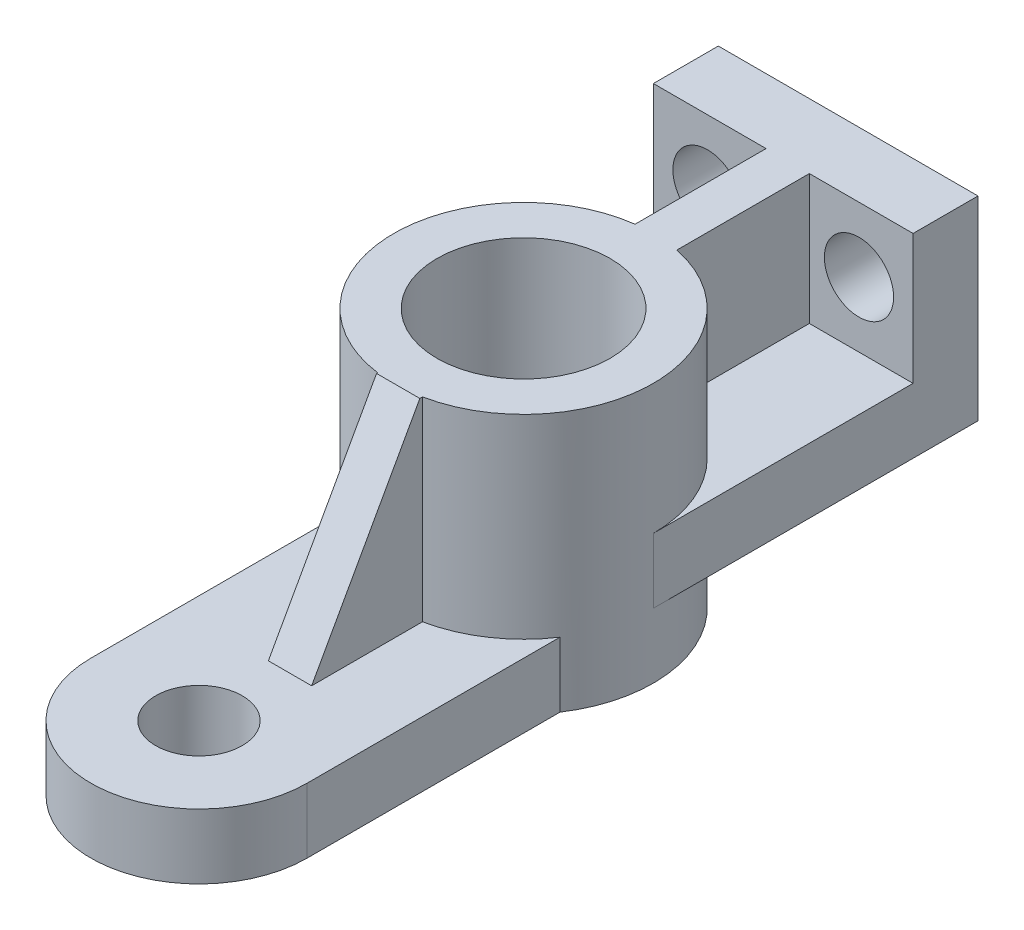
SolidWorks part; units mm, degrees
ref_plane "Front" through (0, 0, 0) normal (0, 0, 1) x (1, 0, 0)
ref_plane "Top" through (0, 0, 0) normal (0, 1, 0) x (1, 0, 0)
ref_plane "Right" through (0, 0, 0) normal (1, 0, 0) x (0, 0, -1)
sketch "Sketch1" plane through (0, 0, 0) normal (0, 0, 1) x (1, 0, 0)
  line L1 (0, 0) -> (-1524, 0)
  line L2 (0, 0) -> (0, 1143)
  line L3 (0, 1143) -> (-1524, 1143)
  line L4 (-1524, 0) -> (-1524, 1143)
  dimension "D1" = 1524
  dimension "D2" = 1143
extrude "Boss-Extrude1" add sketch "Sketch1" along normal blind 381
sketch "Sketch4" plane through (0, 0, 381) normal (0, 0, 1) x (1, 0, 0)
  line L0 (-1206.5, 762) -> (-317.5, 762) construction
  line L1 (0, 1143) -> (-1524, 1143) construction
  line L2 (-1524, 1143) -> (-1524, 0) construction
  circle A0 centre (-317.5, 762) radius 203.2
  circle A1 centre (-1206.5, 762) radius 203.2
  point P4 (-762, 762)
  point P7 (0, 0)
  dimension "D1" = 406.4
  dimension "D4" = 762
  dimension "D2" = 381
  dimension "D3" = 889
extrude "Cut-Extrude1" cut sketch "Sketch4" against normal through all
sketch "Sketch5" plane through (0, 1143, 0) normal (0, 1, 0) x (1, 0, 0)
  line L0 (0, -381) -> (-1524, -381) construction
  line L1 (-1524, -381) -> (-1524, 0) construction
  circle A0 centre (-762, -1905) radius 762
  dimension "D1" = 1524
  dimension "D2" = 1524
extrude "Boss-Extrude2" add sketch "Sketch5" against normal blind 1524 separate body
sketch "Sketch6" plane through (0, 0, 381) normal (0, 0, 1) x (1, 0, 0)
  line L0 (-1524, 1143) -> (-1524, 0) construction
  line L1 (0, 0) -> (-1524, 0)
  line L2 (0, 0) -> (0, 381)
  line L3 (0, 381) -> (-1524, 381)
  line L4 (-1524, 0) -> (-1524, 381)
  dimension "D1" = 381
extrude "Boss-Extrude3" add sketch "Sketch6" along normal blind 1524
sketch "Sketch8" plane through (0, 381, 0) normal (0, 1, 0) x (1, 0, 0)
  line L0 (0, -381) -> (-1524, -381) construction
  line L1 (-608.7231, -381) -> (-862.7231, -381)
  line L2 (-608.7231, -381) -> (-608.7231, -1168.4)
  line L3 (-608.7231, -1168.4) -> (-862.7231, -1168.4)
  line L4 (-862.7231, -381) -> (-862.7231, -1168.4)
  dimension "D1" = 254
  dimension "D2" = 787.4
extrude "Boss-Extrude4" add sketch "Sketch8" along normal up to surface (762 mm away) up to face at (-1524, 1143, 1905)
ref_plane "Plane1" through (0, 0, 2667) normal (0, 0, 1) x (1, 0, 0)
ref_plane "Plane2" through (0, 0, 1143) normal (0, 0, -1) x (-1, 0, 0)
ref_plane "Plane3" through (0, 0, 1905) normal (0, 0, 1) x (1, 0, 0)
sketch "Sketch10" plane through (0, 0, 1905) normal (0, 0, 1) x (1, 0, 0)
  line L1 (-127, -381) -> (-1397, -381)
  line L2 (-127, -381) -> (-127, 0)
  line L3 (-127, 0) -> (-1397, 0)
  line L4 (-1397, -381) -> (-1397, 0)
  line L8 (0, 0) -> (0, 381) construction
  line L10 (-1524, -381) -> (0, -381) construction
  dimension "D1" = 1270
  dimension "D2" = 381
  dimension "D3" = 127
extrude "Boss-Extrude5" add sketch "Sketch10" along normal blind 1905
sketch "Sketch11" plane through (0, 0, 0) normal (0, 1, 0) x (1, 0, 0)
  line L0 (-127, -3810) -> (-1397, -3810) construction
  circle A0 centre (-762, -3810) radius 635
  dimension "D1" = 1270
extrude "Boss-Extrude6" add sketch "Sketch11" against normal up to surface (381 mm away)
sketch "Sketch12" plane through (0, 0, 0) normal (0, 1, 0) x (1, 0, 0)
  circle A0 centre (-762, -3810) radius 254
  arc A1 (-1397, -3810) -> (-127, -3810) centre (-762, -3810) ccw construction
  point P5 (0, 0)
  point P7 (-538.2617, -3538.614)
  point P8 (-776.5512, -3810.0021)
  point P9 (-775.088, -4064)
  point P10 (-1005.8703, -3916.0921)
  dimension "D1" = 508
extrude "Cut-Extrude2" cut sketch "Sketch12" along normal through all and the other way through all
sketch "Sketch13" plane through (-862.7231, 0, 0) normal (-1, 0, 0) x (0, 0, 1)
  line L0 (2666.9746, 1143) -> (2666.9746, 0)
  line L1 (2666.9746, 0) -> (3301.9746, 0)
  line L2 (3301.9746, 0) -> (2666.9746, 1143)
  line L3 (3810, 0) -> (2326.2113, 0) construction
  line L7 (0, 1143) -> (0, 0) construction
  point P5 (0, 0)
  dimension "D1" = 635
  dimension "D2" = 1143
  dimension "D3" = 2666.9746
extrude "Boss-Extrude10" add sketch "Sketch13" against normal blind 254
sketch "Sketch14" plane through (0, 0, 2666.9746) normal (0, 0, -1) x (-1, 0, 0)
  line L0 (608.7231, 1143) -> (755.7783, 1143) construction
  line L1 (608.7231, 1143) -> (862.7231, 1143)
  line L2 (608.7231, 1143) -> (608.7231, 0)
  line L3 (608.7231, 0) -> (862.7231, 0)
  line L4 (862.7231, 1143) -> (862.7231, 0)
  line L5 (862.7231, 0) -> (768.2217, 0) construction
  line L7 (608.7231, 1143) -> (608.7231, 0) construction
  line L8 (862.7231, 1143) -> (862.7231, 0) construction
extrude "Boss-Extrude11" add sketch "Sketch14" along normal blind 25.4
sketch "Sketch15" plane through (0, 1143, 0) normal (0, 1, 0) x (1, 0, 0)
  circle A0 centre (-762, -1905) radius 508
  arc A1 (-608.7231, -2651.4249) -> (-608.7231, -1158.5751) centre (-762, -1905) ccw construction
  dimension "D1" = 1016
extrude "Cut-Extrude3" cut sketch "Sketch15" against normal through all both and the other way through all
